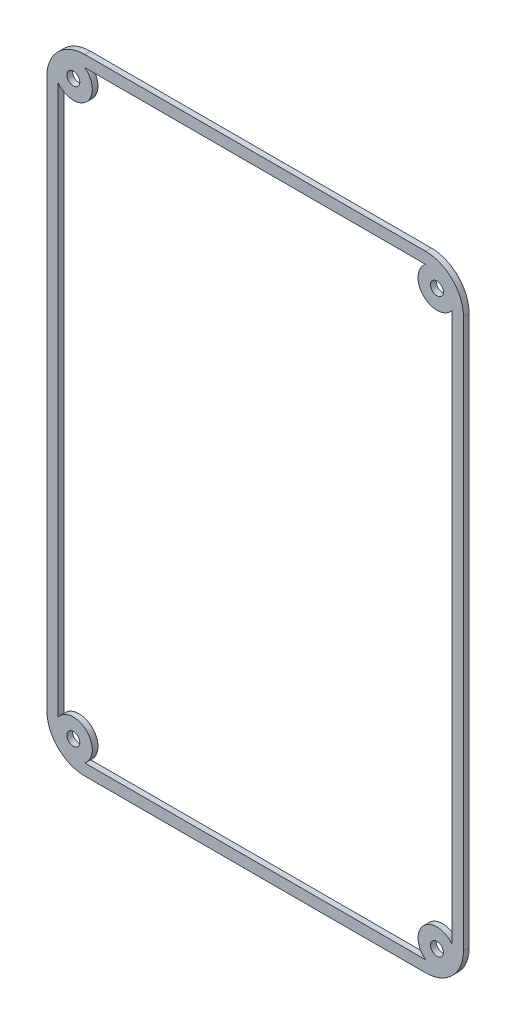
SolidWorks part; units mm, degrees
material "Rubber"
ref_plane "Front Plane" through (0, 0, 0) normal (0, 0, 1) x (1, 0, 0)
ref_plane "Top Plane" through (0, 0, 0) normal (0, 1, 0) x (1, 0, 0)
ref_plane "Right Plane" through (0, 0, 0) normal (1, 0, 0) x (0, 0, -1)
sketch "Sketch1" plane through (0, 0, 0) normal (0, 0, 1) x (1, 0, 0)
  line L0 (-45, -82.5) -> (45, -82.5)
  line L1 (55, -72.5) -> (55, 72.5)
  line L2 (45, 82.5) -> (-45, 82.5)
  line L3 (-55, 72.5) -> (-55, -72.5)
  line L4 (-45, -79.5) -> (45, -79.5)
  line L5 (52, -72.5) -> (52, 72.5)
  line L6 (45, 79.5) -> (-45, 79.5)
  line L7 (-52, 72.5) -> (-52, -72.5)
  arc A0 (45, -82.5) -> (55, -72.5) centre (45, -72.5) ccw
  arc A1 (55, 72.5) -> (45, 82.5) centre (45, 72.5) ccw
  arc A2 (-45, 82.5) -> (-55, 72.5) centre (-45, 72.5) ccw
  arc A3 (-55, -72.5) -> (-45, -82.5) centre (-45, -72.5) ccw
  arc A4 (45, -79.5) -> (52, -72.5) centre (45, -72.5) ccw
  arc A5 (52, 72.5) -> (45, 79.5) centre (45, 72.5) ccw
  arc A6 (-45, 79.5) -> (-52, 72.5) centre (-45, 72.5) ccw
  arc A7 (-52, -72.5) -> (-45, -79.5) centre (-45, -72.5) ccw
extrude "Boss-Extrude1" add sketch "Sketch1" along normal blind 1.5
sketch "Sketch2" plane through (0, 0, 0) normal (0, 0, 1) x (1, 0, 0)
  circle A0 centre (-48, -75.5) radius 5
  circle A1 centre (-48, 75.5) radius 5
  circle A2 centre (48, -75.5) radius 5
  circle A3 centre (48, 75.5) radius 5
extrude "Boss-Extrude2" add sketch "Sketch2" along normal blind 1.5
sketch "Sketch3" plane through (0, 0, 1.5) normal (0, 0, 1) x (1, 0, 0)
  circle A0 centre (-48, -75.5) radius 1.7
  circle A1 centre (-48, 75.5) radius 1.7
  circle A2 centre (48, -75.5) radius 1.7
  circle A3 centre (48, 75.5) radius 1.7
extrude "Cut-Extrude1" cut sketch "Sketch3" against normal through all
